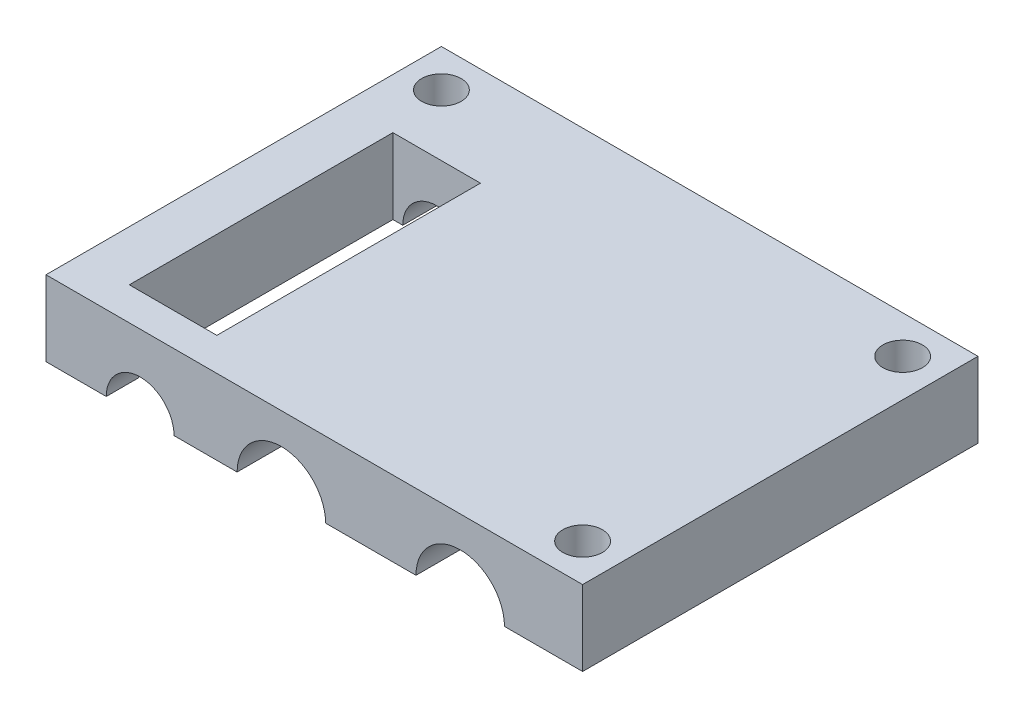
SolidWorks part; units mm, degrees
ref_plane "Alzado" through (0, 0, 0) normal (0, 0, 1) x (1, 0, 0)
ref_plane "Planta" through (0, 0, 0) normal (0, 1, 0) x (1, 0, 0)
ref_plane "Vista lateral" through (0, 0, 0) normal (1, 0, 0) x (0, 0, -1)
sketch "Croquis1" plane through (0, 0, 0) normal (0, 0, 1) x (1, 0, 0)
  line L0 (-28.5, 0) -> (-22.1, 0)
  line L1 (-28.5, 8) -> (28.5, 8)
  line L2 (-28.5, 8) -> (-28.5, -8)
  line L3 (-28.5, -8) -> (28.5, -8)
  line L4 (28.5, 8) -> (28.5, -8)
  line L5 (-28.5, 8) -> (28.5, -8) construction
  line L6 (-28.5, -8) -> (28.5, 8) construction
  line L7 (-14.9, 0) -> (-8.2, 0)
  line L8 (1.2, 0) -> (10.8, 0)
  line L9 (20.2, 0) -> (28.5, 0)
  circle A1 centre (-18.5, 0) radius 3.6
  circle A2 centre (-3.5, 0) radius 4.7
  circle A3 centre (15.5, 0) radius 4.7
  point P0 (0, 0)
  dimension "D1" = 16
  dimension "D3" = 7.2
  dimension "D5" = 9.4
  dimension "D6" = 15
  dimension "D7" = 9.4
  dimension "D2" = 57
  dimension "D4" = 10
  dimension "D8" = 19
extrude "Saliente-Extruir1" add sketch "Croquis1" against normal blind 42 contours A3 L9 L4 L1 L2 L0 A1 L7 A2 L8
sketch "Croquis2" plane through (0, 8, 0) normal (0, 1, 0) x (1, 0, 0)
  line L0 (-18.5, 0) -> (-18.5, 42) construction
  line L1 (-22.1, 0) -> (-14.9, 0) construction
  line L2 (-28.5, 42) -> (28.5, 42) construction
  line L4 (-28.5, 0) -> (28.5, 0) construction
  line L5 (-23.15, 31.5) -> (-13.85, 31.5)
  line L6 (-23.15, 31.5) -> (-23.15, 3.5)
  line L7 (-23.15, 3.5) -> (-13.85, 3.5)
  line L8 (-13.85, 31.5) -> (-13.85, 3.5)
  line L9 (-23.15, 31.5) -> (-13.85, 3.5) construction
  line L10 (-23.15, 3.5) -> (-13.85, 31.5) construction
  point P8 (-18.5, 17.5)
  dimension "D1" = 9.3
  dimension "D2" = 3.5
  dimension "D3" = 28
extrude "Cortar-Extruir1" cut sketch "Croquis2" against normal blind 50
sketch "Croquis3" plane through (0, 8, 0) normal (0, 1, 0) x (1, 0, 0)
  line L0 (-28.5, 42) -> (28.5, 42) construction
  line L1 (-28.5, 42) -> (-28.5, 0) construction
  line L2 (28.5, 42) -> (28.5, 0) construction
  line L3 (-28.5, 0) -> (28.5, 0) construction
  circle A0 centre (-24.5, 38) radius 2.1
  circle A1 centre (24.5, 38) radius 2.1
  circle A2 centre (24.5, 4) radius 2.1
  dimension "D1" = 4.2
  dimension "D5" = 4.2
  dimension "D6" = 4.2
  dimension "D2" = 4
  dimension "D3" = 4
  dimension "D4" = 4
  dimension "D7" = 4
extrude "Cortar-Extruir2" cut sketch "Croquis3" against normal blind 50
sketch "Croquis4" plane through (0, 0, -42) normal (0, 0, -1) x (-1, 0, 0)
  line L0 (-20.2, 0) -> (-17, 0)
  line L1 (-14, 0) -> (-10.8, 0)
  line L2 (-1.2, 0) -> (2, 0)
  line L3 (5, 0) -> (8.2, 0)
  line L4 (14.9, 0) -> (16.5, 0)
  line L5 (20.5, 0) -> (22.1, 0)
  circle A0 centre (-15.5, 0) radius 1.5
  circle A1 centre (-15.5, 0) radius 4.7
  circle A2 centre (3.5, 0) radius 1.5
  circle A3 centre (18.5, 0) radius 2
  arc A4 (8.2, 0) -> (-1.2, 0) centre (3.5, 0) ccw construction
  arc A5 (22.1, 0) -> (14.9, 0) centre (18.5, 0) ccw construction
  arc A6 (8.2, 0) -> (-1.2, 0) centre (3.5, 0) ccw
  arc A7 (22.1, 0) -> (14.9, 0) centre (18.5, 0) ccw
  arc M4 (-20.2, 0) -> (-10.8, 0) centre (-15.5, 0) cw
  arc M6 (-1.2, 0) -> (8.2, 0) centre (3.5, 0) cw
  arc M8 (14.9, 0) -> (22.1, 0) centre (18.5, 0) cw
  dimension "D1" = 3
  dimension "D2" = 4
  dimension "D3" = 3
extrude "Saliente-Extruir2" add sketch "Croquis4" against normal blind 3 contours A0 L1 L0 M4 | A2 L3 L2 M6 | A3 L5 L4 M8
